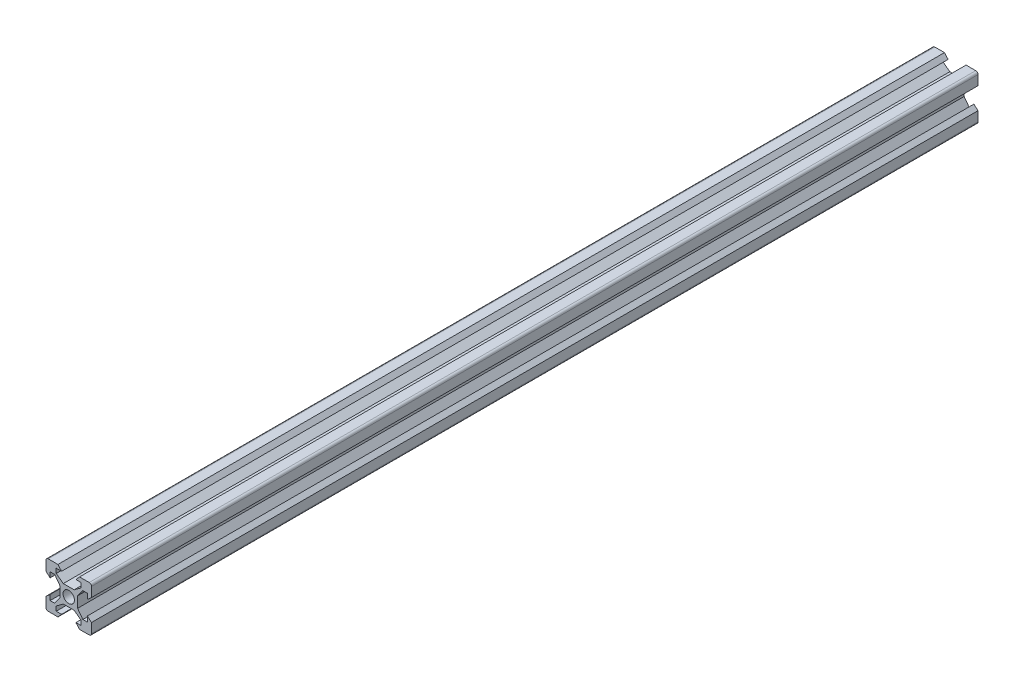
SolidWorks part; units mm, degrees
ref_plane "Front Plane" through (0, 0, 0) normal (0, 0, 1) x (1, 0, 0)
ref_plane "Top Plane" through (0, 0, 0) normal (0, 1, 0) x (1, 0, 0)
ref_plane "Right Plane" through (0, 0, 0) normal (1, 0, 0) x (0, 0, -1)
sketch "Sketch1" plane through (0, 0, 0) normal (0, 0, 1) x (1, 0, 0)
  line L0 (-5.5, 8.2) -> (-3.15, 8.2)
  line L5 (-10, -10) -> (10, 10) construction
  line L6 (-10, 10) -> (10, -10) construction
  line L7 (-9, 10) -> (-4.75, 10)
  line L8 (4.75, 10) -> (9, 10)
  line L9 (-4.75, 10) -> (-3.15, 8.2)
  line L10 (4.75, 10) -> (3.15, 8.2)
  line L11 (3.15, 8.2) -> (5.5, 8.2)
  line L12 (-5.5, 8.2) -> (-5.5, 6.2)
  line L13 (5.5, 8.2) -> (5.5, 6.2)
  line L14 (2.3879, 3.9) -> (-2.3879, 3.9)
  line L15 (-5.5, 6.2) -> (-2.3879, 3.9)
  line L16 (2.3879, 3.9) -> (5.5, 6.2)
  line L17 (10, 9) -> (10, 4.75)
  line L18 (10, 4.75) -> (8.2, 3.15)
  line L19 (10, -4.75) -> (8.2, -3.15)
  line L20 (8.2, -3.15) -> (8.2, -5.5)
  line L21 (8.2, 5.5) -> (8.2, 3.15)
  line L22 (8.2, 5.5) -> (6.2, 5.5)
  line L23 (6.2, 5.5) -> (3.9, 2.3879)
  line L24 (3.9, -2.3879) -> (3.9, 2.3879)
  line L25 (3.9, -2.3879) -> (6.2, -5.5)
  line L26 (8.2, -5.5) -> (6.2, -5.5)
  line L27 (10, -4.75) -> (10, -9)
  line L28 (9, -10) -> (4.75, -10)
  line L29 (4.75, -10) -> (3.15, -8.2)
  line L30 (-4.75, -10) -> (-3.15, -8.2)
  line L31 (-3.15, -8.2) -> (-5.5, -8.2)
  line L32 (5.5, -8.2) -> (3.15, -8.2)
  line L33 (5.5, -8.2) -> (5.5, -6.2)
  line L34 (5.5, -6.2) -> (2.3879, -3.9)
  line L35 (-2.3879, -3.9) -> (2.3879, -3.9)
  line L36 (-2.3879, -3.9) -> (-5.5, -6.2)
  line L37 (-5.5, -8.2) -> (-5.5, -6.2)
  line L38 (-4.75, -10) -> (-9, -10)
  line L39 (-10, -9) -> (-10, -4.75)
  line L40 (-10, -4.75) -> (-8.2, -3.15)
  line L41 (-10, 4.75) -> (-8.2, 3.15)
  line L42 (-8.2, 3.15) -> (-8.2, 5.5)
  line L43 (-8.2, -5.5) -> (-8.2, -3.15)
  line L44 (-8.2, -5.5) -> (-6.2, -5.5)
  line L45 (-6.2, -5.5) -> (-3.9, -2.3879)
  line L46 (-3.9, 2.3879) -> (-3.9, -2.3879)
  line L47 (-3.9, 2.3879) -> (-6.2, 5.5)
  line L48 (-8.2, 5.5) -> (-6.2, 5.5)
  line L49 (-10, 4.75) -> (-10, 9)
  arc A0 (9, 10) -> (10, 9) centre (9, 9) cw
  arc A1 (9, -10) -> (10, -9) centre (9, -9) ccw
  arc A2 (-9, -10) -> (-10, -9) centre (-9, -9) cw
  arc A3 (-10, 9) -> (-9, 10) centre (-9, 9) cw
  circle A4 centre (0, 0) radius 2.5
  point P0 (0, 0)
  point P21 (0, 10)
  point P24 (0, 8.2)
  point P27 (0, 8.2)
  point P32 (0, 3.9)
  point P71 (0, 0)
  dimension "D3" = 1
  dimension "D12" = 5
  dimension "D1" = 20
  dimension "D2" = 20
  dimension "D4" = 9.5
  dimension "D5" = 6.3
  dimension "D6" = 0
  dimension "D7" = 10
  dimension "D8" = 6.1
  dimension "D9" = 11
  dimension "D10" = 2
  dimension "D11" = 4
extrude "Boss-Extrude1" add sketch "Sketch1" along normal blind 390
